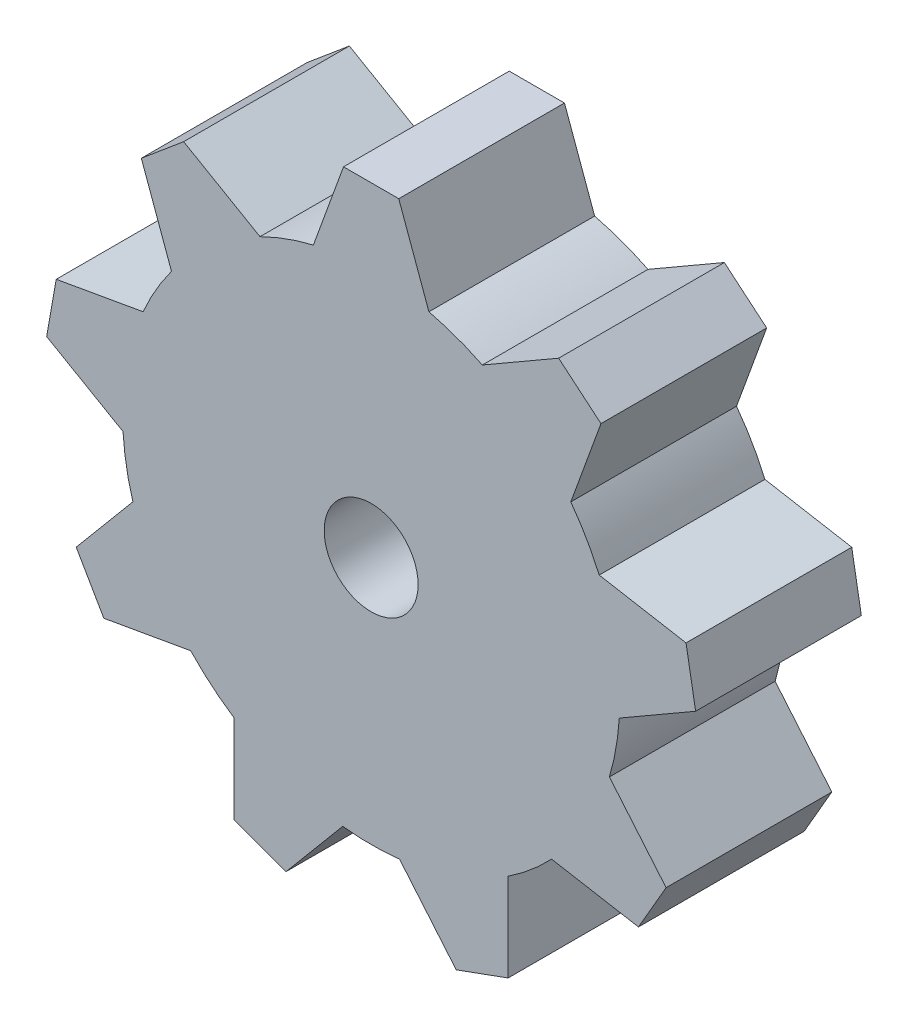
SolidWorks part; units mm, degrees
ref_plane "Front Plane" through (0, 0, 0) normal (0, 0, 1) x (1, 0, 0)
ref_plane "Top Plane" through (0, 0, 0) normal (0, 1, 0) x (1, 0, 0)
ref_plane "Right Plane" through (0, 0, 0) normal (1, 0, 0) x (0, 0, -1)
sketch "Sketch1" plane through (0, 0, 0) normal (0, 0, 1) x (1, 0, 0)
  line L0 (2.0121, 4.0251) -> (3.3945, 4.8232)
  line L1 (-1.046, 4.3768) -> (-0.5, 5.8768)
  line L2 (-0.5, 5.8768) -> (0.5, 5.8768)
  line L3 (0.5, 5.8768) -> (1.046, 4.3768)
  line L4 (3.3945, 4.8232) -> (4.1605, 4.1805)
  line L5 (4.1605, 4.1805) -> (3.6146, 2.6805)
  line L6 (4.1286, 1.7901) -> (5.7006, 1.5129)
  line L7 (5.7006, 1.5129) -> (5.8743, 0.5281)
  line L8 (5.8743, 0.5281) -> (4.4919, -0.27)
  line L9 (4.3134, -1.2826) -> (5.3394, -2.5054)
  line L10 (5.3394, -2.5054) -> (4.8394, -3.3714)
  line L11 (4.8394, -3.3714) -> (3.2674, -3.0942)
  line L12 (2.4798, -3.7551) -> (2.4798, -5.3513)
  line L13 (2.4798, -5.3513) -> (1.5401, -5.6934)
  line L14 (1.5401, -5.6934) -> (0.5141, -4.4705)
  line L15 (-0.5141, -4.4705) -> (-1.5401, -5.6934)
  line L16 (-1.5401, -5.6934) -> (-2.4798, -5.3513)
  line L17 (-2.4798, -5.3513) -> (-2.4798, -3.7551)
  line L18 (-3.2674, -3.0942) -> (-4.8394, -3.3714)
  line L19 (-4.8394, -3.3714) -> (-5.3394, -2.5054)
  line L20 (-5.3394, -2.5054) -> (-4.3134, -1.2826)
  line L21 (-4.4919, -0.27) -> (-5.8743, 0.5281)
  line L22 (-5.8743, 0.5281) -> (-5.7006, 1.5129)
  line L23 (-5.7006, 1.5129) -> (-4.1286, 1.7901)
  line L24 (-3.6146, 2.6805) -> (-4.1605, 4.1805)
  line L25 (-4.1605, 4.1805) -> (-3.3945, 4.8232)
  line L26 (-3.3945, 4.8232) -> (-2.0121, 4.0251)
  arc A0 (-4.4919, -0.27) -> (-4.3134, -1.2826) centre (0, 0) ccw
  circle A1 centre (0, 0) radius 0.85
  arc A2 (-3.6146, 2.6805) -> (-4.1286, 1.7901) centre (0, 0) ccw
  arc A3 (-1.046, 4.3768) -> (-2.0121, 4.0251) centre (0, 0) ccw
  arc A4 (2.0121, 4.0251) -> (1.046, 4.3768) centre (0, 0) ccw
  arc A5 (4.1286, 1.7901) -> (3.6146, 2.6805) centre (0, 0) ccw
  arc A6 (4.3134, -1.2826) -> (4.4919, -0.27) centre (0, 0) ccw
  arc A7 (2.4798, -3.7551) -> (3.2674, -3.0942) centre (0, 0) ccw
  arc A8 (-0.5141, -4.4705) -> (0.5141, -4.4705) centre (0, 0) ccw
  arc A9 (-3.2674, -3.0942) -> (-2.4798, -3.7551) centre (0, 0) ccw
  point P42 (0, 0)
  dimension "D1" = 9
  dimension "D2" = 1.7
  dimension "D3" = 110
  dimension "D4" = 110
  dimension "D5" = 1
  dimension "D7" = 1.5
  dimension "D6" = 9
extrude "Boss-Extrude1" add sketch "Sketch1" along normal blind 3
